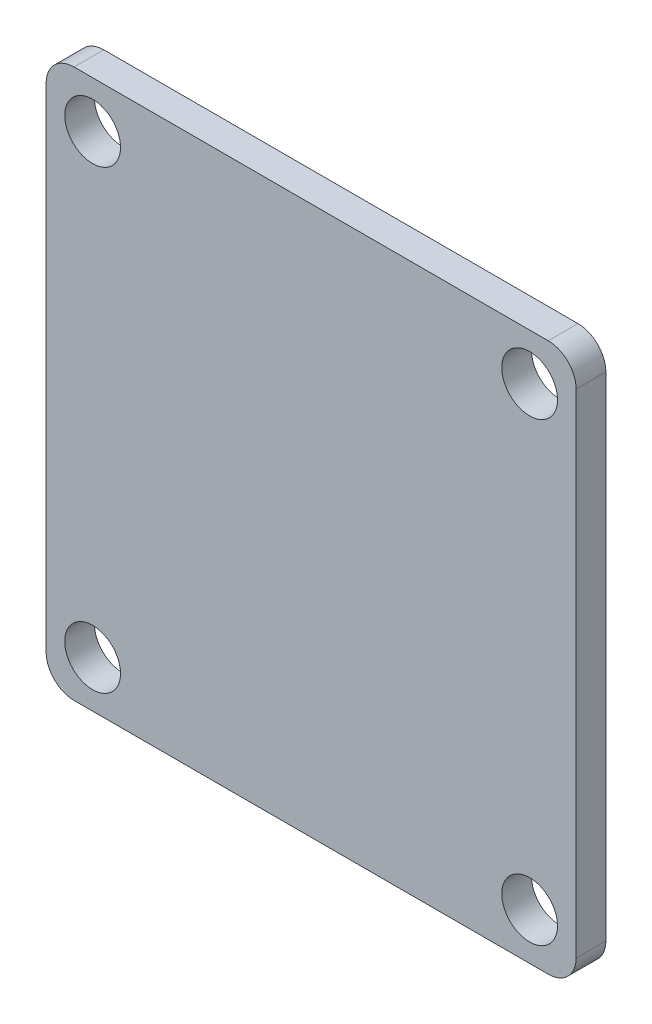
SolidWorks part; units mm, degrees
ref_plane "前视基准面" through (0, 0, 0) normal (0, 0, 1) x (1, 0, 0)
ref_plane "上视基准面" through (0, 0, 0) normal (0, 1, 0) x (1, 0, 0)
ref_plane "右视基准面" through (0, 0, 0) normal (1, 0, 0) x (0, 0, -1)
sketch "草图1" plane through (0, 0, 0) normal (0, 0, 1) x (1, 0, 0)
  line L0 (0, 0) -> (28.5, 0)
  line L1 (0, 0) -> (0, 29.5)
  line L2 (0, 29.5) -> (2.5, 29.5)
  line L3 (28.5, 29.5) -> (28.5, 0)
  line L7 (2.5, 29.5) -> (28.5, 29.5)
  circle A0 centre (2.5, 27) radius 1.5
  circle A1 centre (26, 27) radius 1.5
  circle A2 centre (26, 2.5) radius 1.5
  circle A3 centre (2.5, 2.5) radius 1.5
extrude "凸台-拉伸1" add sketch "草图1" along normal blind 1.6
fillet "圆角1" radius 1.5 4 edges at (0, 29.5, 0.8) (0, 0, 0.8) (28.5, 0, 0.8) (28.5, 29.5, 0.8)
